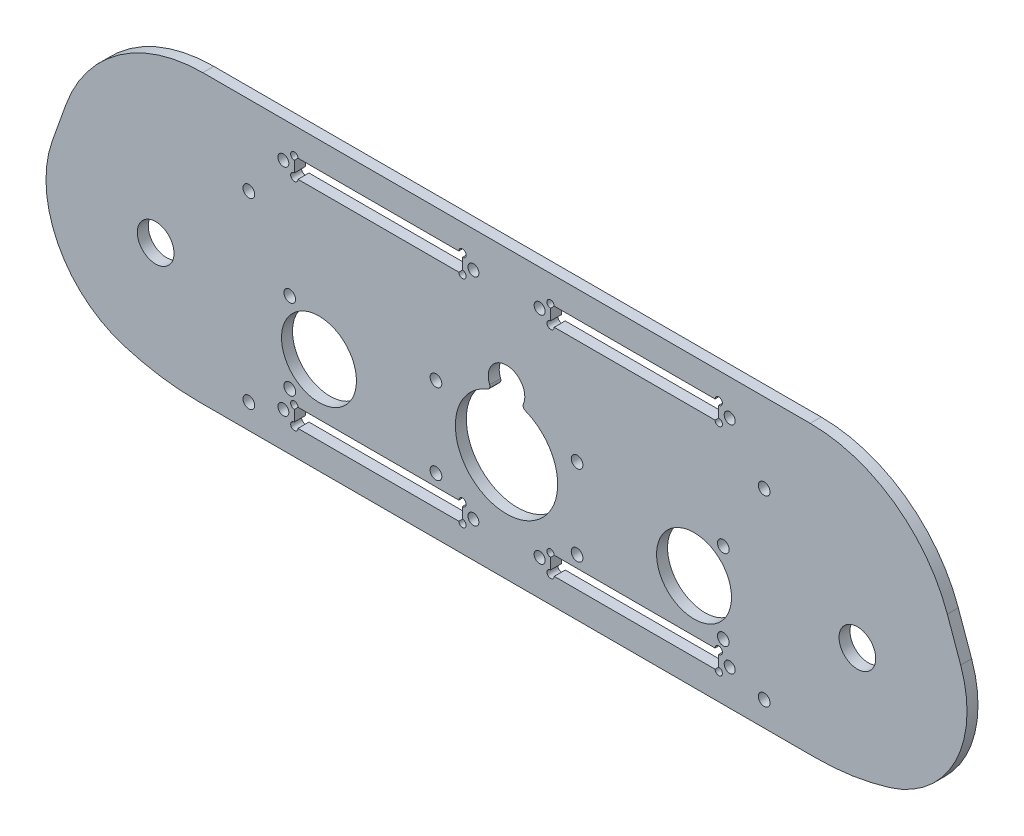
SolidWorks part; units mm, degrees
material "5052-O"
ref_plane "正面" through (0, 0, 0) normal (0, 0, 1) x (1, 0, 0)
ref_plane "平面" through (0, 0, 0) normal (0, 1, 0) x (1, 0, 0)
ref_plane "右側面" through (0, 0, 0) normal (1, 0, 0) x (0, 0, -1)
sketch "ｽｹｯﾁ1" plane through (0, 0, 0) normal (0, 0, 1) x (1, 0, 0)
  line L0 (96, 0) -> (-96, 0) construction
  line L1 (96, -30) -> (-96, -30)
  line L2 (96, 30) -> (-96, 30)
  arc A0 (96, -30) -> (96, 30) centre (96, 0) ccw
  arc A1 (-96, 30) -> (-96, -30) centre (-96, 0) ccw
  circle A2 centre (-96, 0) radius 5.025
  circle A3 centre (96, 0) radius 5.025
  point P2 (0, 0)
  dimension "D2" = 30
  dimension "D3" = 10.05
  dimension "D1" = 192
extrude "ﾎﾞｽ - 押し出し1" add sketch "ｽｹｯﾁ1" along normal blind 3
sketch "ｽｹｯﾁ2" plane through (0, 0, 3) normal (0, 0, 1) x (1, 0, 0)
  line L0 (-96, -30) -> (96, -30) construction
  line L1 (96, 30) -> (-96, 30) construction
  line L3 (-16.0573, -19.5) -> (-62.5573, -19.5) construction
  line L4 (-16.0573, -19.5) -> (-16.0573, 9) construction
  line L5 (-16.0573, 9) -> (-62.5573, 9) construction
  line L6 (-62.5573, -19.5) -> (-62.5573, 9) construction
  line L7 (-16.0573, -19.5) -> (-62.5573, 9) construction
  line L8 (-16.0573, 9) -> (-62.5573, -19.5) construction
  line L9 (70.5, -25) -> (-70.5, -25) construction
  line L10 (0, 30) -> (0, -30) construction
  line L11 (16.0573, 9) -> (62.5573, -19.5) construction
  line L12 (16.0573, -19.5) -> (62.5573, 9) construction
  line L13 (62.5573, -19.5) -> (62.5573, 9) construction
  line L14 (16.0573, 9) -> (62.5573, 9) construction
  line L15 (16.0573, -19.5) -> (16.0573, 9) construction
  line L16 (16.0573, -19.5) -> (62.5573, -19.5) construction
  line L17 (19.3073, 5.75) -> (59.3073, 5.75) construction
  line L18 (-19.3073, -16.25) -> (-59.3073, -16.25) construction
  line L19 (-19.3073, -16.25) -> (-19.3073, 5.75) construction
  line L20 (-19.3073, 5.75) -> (-59.3073, 5.75) construction
  line L21 (-59.3073, -16.25) -> (-59.3073, 5.75) construction
  line L22 (-19.3073, -16.25) -> (-59.3073, 5.75) construction
  line L23 (-19.3073, 5.75) -> (-59.3073, -16.25) construction
  line L24 (59.3073, -16.25) -> (59.3073, 5.75) construction
  line L25 (19.3073, -16.25) -> (59.3073, -16.25) construction
  line L26 (19.3073, -16.25) -> (19.3073, 5.75) construction
  line L27 (51.3073, -5.25) -> (-51.3073, -5.25) construction
  line L28 (70.5, -25) -> (70.5, 25) construction
  line L29 (70.5, 25) -> (-70.5, 25) construction
  line L30 (-70.5, -25) -> (-70.5, 25) construction
  line L31 (70.5, -25) -> (-70.5, 25) construction
  line L32 (70.5, 25) -> (-70.5, -25) construction
  arc A0 (-96, 30) -> (-96, -30) centre (-96, 0) cw construction
  arc A1 (-96, 30) -> (-96, -30) centre (-96, 0) ccw construction
  arc A2 (96, 30) -> (96, -30) centre (96, 0) ccw construction
  arc A3 (96, -30) -> (96, 30) centre (96, 0) ccw construction
  circle A6 centre (-59.3073, 5.75) radius 1.6
  circle A7 centre (-59.3073, -16.25) radius 1.6
  circle A8 centre (-19.3073, -16.25) radius 1.6
  circle A9 centre (-19.3073, 5.75) radius 1.6
  circle A10 centre (19.3073, 5.75) radius 1.6
  circle A11 centre (19.3073, -16.25) radius 1.6
  circle A12 centre (59.3073, 5.75) radius 1.6
  circle A13 centre (59.3073, -16.25) radius 1.6
  circle A14 centre (51.3073, -5.25) radius 10.25
  circle A15 centre (-51.3073, -5.25) radius 10.25
  circle A16 centre (-70.5, 25) radius 1.6
  arc A17 (-84.8645, 30) -> (-84.8645, -30) centre (-96, 0) cw construction
  circle A18 centre (0, -2.25) radius 14
  circle A19 centre (0, -2.25) radius 16 construction
  circle A20 centre (-96, 0) radius 5.025 construction
  circle A21 centre (-70.5, -25) radius 1.6
  circle A22 centre (70.5, -25) radius 1.6
  circle A23 centre (70.5, 25) radius 1.6
  point P23 (-39.3073, -5.25)
  point P28 (0, 0)
  point P38 (39.3073, -5.25)
  point P39 (-39.3073, -5.25)
  point P62 (-19.3073, -5.25)
  point P63 (16.0573, -5.25)
  dimension "D3" = 28
  dimension "D4" = 27.75
  dimension "D7" = 3.2
  dimension "D10" = 20.5
  dimension "D11" = 45
  dimension "D12" = 32
  dimension "D13" = 32
  dimension "D17" = 3.2
  dimension "D1" = 28.5
  dimension "D2" = 46.5
  dimension "D5" = 22
  dimension "D6" = 40
  dimension "D8" = 11.25
  dimension "D9" = 11.25
  dimension "D14" = 24.75
  dimension "D15" = 50
  dimension "D16" = 141
extrude "ｶｯﾄ - 押し出し1" cut sketch "ｽｹｯﾁ2" against normal through all
sketch "ｽｹｯﾁ4" plane through (0, 0, 3) normal (0, 0, 1) x (1, 0, 0)
  line L0 (-124.2607, 10.0665) -> (-120.6113, 20.3117)
  line L1 (-83.1, 46.77) -> (83.1, 46.77)
  line L2 (120.6113, 20.3117) -> (124.2607, 10.0665)
  line L3 (96, 30) -> (-96, 30) construction
  line L4 (-96, 30) -> (96, 30)
  line L5 (-84.298, -31.75) -> (84.298, -31.75)
  line L6 (-96, -30) -> (96, -30) construction
  line L7 (96, -30) -> (-96, -30)
  arc A0 (-96, 30) -> (-96, -30) centre (-96, 0) ccw construction
  arc A1 (-120.6113, 20.3117) -> (-83.1, 46.77) centre (-83.1, 6.95) cw
  arc A2 (83.1, 46.77) -> (120.6113, 20.3117) centre (83.1, 6.95) cw
  arc A3 (96, -30) -> (96, 30) centre (96, 0) ccw construction
  arc A4 (-124.2607, 10.0665) -> (-96, 30) centre (-96, 0) cw
  arc A5 (124.2607, 10.0665) -> (96, 30) centre (96, 0) ccw
  arc A6 (-84.298, -31.75) -> (-104.7765, -28.6875) centre (-84.298, 38.25) cw
  arc A7 (-104.7765, -28.6875) -> (-96, -30) centre (-96, 0) ccw
  arc A8 (84.298, -31.75) -> (104.7765, -28.6875) centre (84.298, 38.25) ccw
  arc A9 (104.7765, -28.6875) -> (96, -30) centre (96, 0) cw
  dimension "D1" = 39.82
  dimension "D5" = 70
  dimension "D2" = 46.77
  dimension "D3" = 166.2
  dimension "D4" = 31.75
extrude "ﾎﾞｽ - 押し出し2" add sketch "ｽｹｯﾁ4" against normal up to surface (3 mm away) up to face at (-57.7073, 5.75, 0)
sketch "ｽｹｯﾁ3" plane through (0, 0, 3) normal (0, 0, 1) x (1, 0, 0)
  line L0 (83.1, 46.77) -> (-83.1, 46.77) construction
  line L1 (-12.0573, 39.52) -> (-58.0573, 39.52)
  line L2 (-12.0573, 39.52) -> (-12.0573, 34.52)
  line L3 (-12.0573, 34.52) -> (-58.0573, 34.52)
  line L4 (-58.0573, 39.52) -> (-58.0573, 34.52)
  line L5 (-12.0573, 39.52) -> (-58.0573, 34.52) construction
  line L6 (-12.0573, 34.52) -> (-58.0573, 39.52) construction
  line L7 (0, 46.77) -> (0, -31.75) construction
  line L9 (-61.0573, 37.02) -> (-58.0573, 37.02) construction
  line L10 (-125.0448, 7.51) -> (125.0448, 7.51) construction
  line L11 (-35.0573, 39.52) -> (-35.0573, 34.52) construction
  line L12 (-35.0573, -24.5) -> (-35.0573, -19.5) construction
  line L13 (-61.0573, -22) -> (-58.0573, -22) construction
  line L14 (-12.0573, -19.5) -> (-58.0573, -24.5) construction
  line L15 (-12.0573, -24.5) -> (-58.0573, -19.5) construction
  line L16 (-58.0573, -24.5) -> (-58.0573, -19.5)
  line L17 (-12.0573, -19.5) -> (-58.0573, -19.5)
  line L18 (-12.0573, -24.5) -> (-12.0573, -19.5)
  line L19 (-12.0573, -24.5) -> (-58.0573, -24.5)
  line L20 (12.0573, -24.5) -> (58.0573, -19.5) construction
  line L21 (12.0573, -19.5) -> (58.0573, -24.5) construction
  line L22 (61.0573, -22) -> (58.0573, -22) construction
  line L23 (35.0573, -24.5) -> (35.0573, -19.5) construction
  line L24 (35.0573, 39.52) -> (35.0573, 34.52) construction
  line L25 (61.0573, 37.02) -> (58.0573, 37.02) construction
  line L26 (12.0573, 34.52) -> (58.0573, 39.52) construction
  line L27 (12.0573, 39.52) -> (58.0573, 34.52) construction
  line L28 (12.0573, -24.5) -> (58.0573, -24.5)
  line L29 (12.0573, -24.5) -> (12.0573, -19.5)
  line L30 (12.0573, -19.5) -> (58.0573, -19.5)
  line L31 (58.0573, -24.5) -> (58.0573, -19.5)
  line L32 (58.0573, 39.52) -> (58.0573, 34.52)
  line L33 (12.0573, 34.52) -> (58.0573, 34.52)
  line L34 (12.0573, 39.52) -> (12.0573, 34.52)
  line L35 (12.0573, 39.52) -> (58.0573, 39.52)
  line L36 (-59.3073, 5.75) -> (-59.3073, -16.25) construction
  line L38 (-84.298, -31.75) -> (84.298, -31.75) construction
  circle A0 centre (-96, 0) radius 32 construction
  circle A1 centre (-61.0573, 37.02) radius 1.5
  circle A2 centre (-9.0573, 37.02) radius 1.5
  circle A5 centre (-9.0573, -22) radius 1.5
  circle A6 centre (-61.0573, -22) radius 1.5
  circle A7 centre (96, 0) radius 32 construction
  circle A8 centre (61.0573, -22) radius 1.5
  circle A9 centre (9.0573, -22) radius 1.5
  circle A10 centre (9.0573, 37.02) radius 1.5
  circle A11 centre (61.0573, 37.02) radius 1.5
  arc A12 (-124.2607, 10.0665) -> (-104.7765, -28.6875) centre (-96, 0) ccw construction
  arc A13 (104.7765, -28.6875) -> (124.2607, 10.0665) centre (96, 0) ccw construction
  point P3 (-35.0573, 37.02)
  point P40 (-35.0573, -22)
  point P65 (35.0573, -22)
  point P66 (35.0573, 37.02)
  point P82 (0, 7.51)
  dimension "D1" = 64
  dimension "D7" = 3
  dimension "D4" = 9.75
  dimension "D5" = 18.1146
  dimension "D2" = 5
  dimension "D3" = 46
  dimension "D6" = 3
extrude "ｶｯﾄ - 押し出し2" cut sketch "ｽｹｯﾁ3" against normal through all
sketch "ｽｹｯﾁ5" plane through (0, 0, 3) normal (0, 0, 1) x (1, 0, 0)
  line L0 (0, 11.75) -> (0, -16.25) construction
  line L1 (-9.0573, 37.02) -> (-9.0573, -22) construction
  line L2 (9.0573, 37.02) -> (9.0573, -22) construction
  line L3 (-9.0573, 7.51) -> (9.0573, 7.51) construction
  circle A0 centre (-58.0573, 39.52) radius 1
  circle A1 centre (-58.0573, 34.52) radius 1
  circle A2 centre (-12.0573, 39.52) radius 1
  circle A3 centre (-12.0573, 34.52) radius 1
  circle A4 centre (0, -2.25) radius 14 construction
  circle A5 centre (12.0573, 34.52) radius 1
  circle A6 centre (12.0573, 39.52) radius 1
  circle A7 centre (58.0573, 34.52) radius 1
  circle A8 centre (58.0573, 39.52) radius 1
  circle A9 centre (58.0573, -24.5) radius 1
  circle A10 centre (58.0573, -19.5) radius 1
  circle A11 centre (12.0573, -24.5) radius 1
  circle A12 centre (12.0573, -19.5) radius 1
  circle A13 centre (-12.0573, -19.5) radius 1
  circle A14 centre (-12.0573, -24.5) radius 1
  circle A15 centre (-58.0573, -19.5) radius 1
  circle A16 centre (-58.0573, -24.5) radius 1
  dimension "D1" = 2
extrude "ｶｯﾄ - 押し出し3" cut sketch "ｽｹｯﾁ5" against normal through all and the other way through all
sketch "ｽｹｯﾁ6" plane through (0, 0, 3) normal (0, 0, 1) x (1, 0, 0)
  line L0 (0, 14) -> (0, 0) construction
  circle A3 centre (0, 14) radius 5
  dimension "D1" = 10
  dimension "D2" = 14
extrude "ｶｯﾄ - 押し出し5" cut sketch "ｽｹｯﾁ6" against normal through all
fillet "ﾌｨﾚｯﾄ1" radius 1 2 edges at (-4.0989, 11.1365, 1.5) (4.0989, 11.1365, 1.5)
